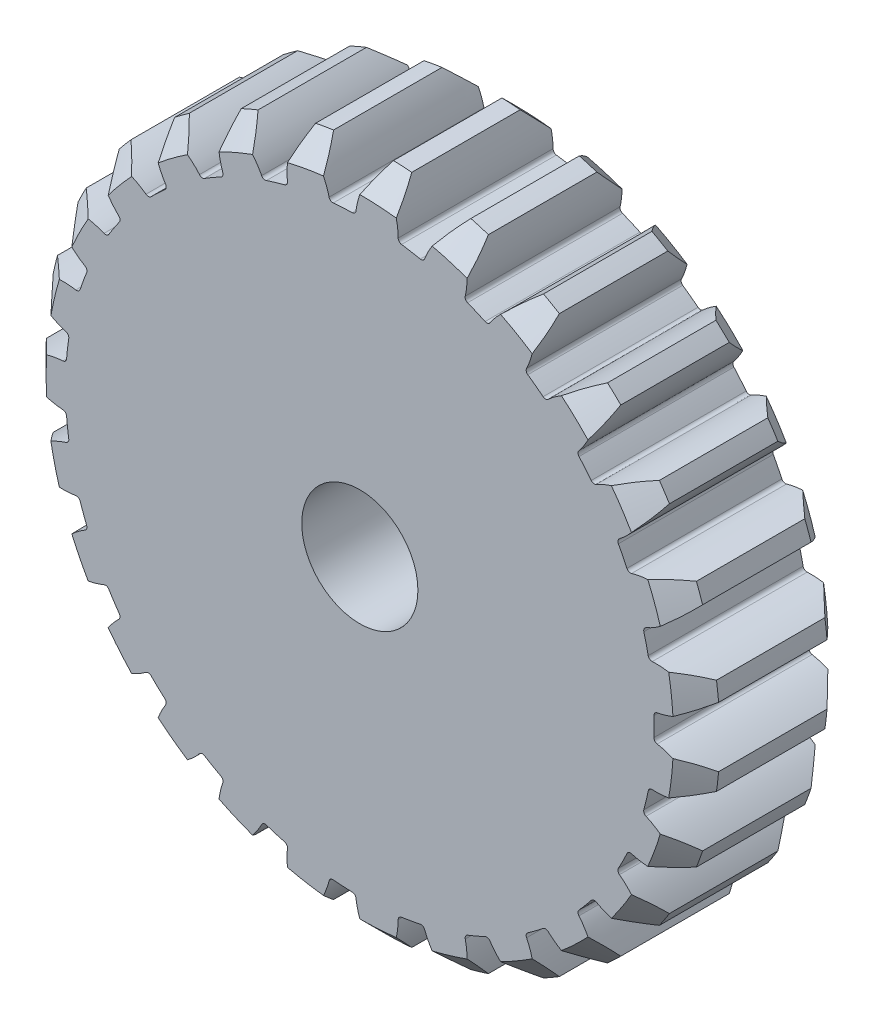
SolidWorks part; units mm, degrees
ref_plane "Piano frontale" through (0, 0, 0) normal (0, 0, 1) x (1, 0, 0)
ref_plane "Piano superiore" through (0, 0, 0) normal (0, 1, 0) x (1, 0, 0)
ref_plane "Piano destro" through (0, 0, 0) normal (1, 0, 0) x (0, 0, -1)
sketch "Schizzo1" plane through (0, 0, 0) normal (0, 0, 1) x (1, 0, 0)
  circle A0 centre (0, 0) radius 7.5
  circle A1 centre (0, 0) radius 43.5
  dimension "D1" = 15
  dimension "D2" = 87
extrude "Estrusione-Estrusione1" add sketch "Schizzo1" along normal blind 20
sketch "Schizzo2" plane through (0, 0, 20) normal (0, 0, 1) x (1, 0, 0)
  line L0 (0, 0) -> (37.9625, 1.6868) construction
  line L1 (0, 0) -> (37.9625, -1.6868) construction
  line L2 (0, 0) -> (38, 0) construction
  arc A0 (37.9625, -1.6868) -> (37.9625, 1.6868) centre (0, 0) ccw
  arc A1 (40.4318, -2.35) -> (40.4318, 2.35) centre (0, 0) ccw
  arc A2 (44.7366, -4.8617) -> (44.7366, 4.8617) centre (0, 0) ccw
  spline S0 degree 4 poles (37.9625, 1.6868) (37.9986, 1.6884) (38.0707, 1.6931) (38.2144, 1.7088) (38.5001, 1.7529) (38.8753, 1.8326) (39.3365, 1.9573) (39.9699, 2.1641) (40.6271, 2.4209) (41.3184, 2.7338) (42.2035, 3.1895) (43.2559, 3.8051) (44.5138, 4.6592) (46.3669, 6.1348) (48.8418, 8.5508) (51.5914, 12.0322) (54.2984, 16.7131) (56.4908, 22.1103) (57.9987, 27.7341) (58.8617, 33.4902) (59.1308, 39.5909) (58.6748, 47.1396) (56.9803, 56.0112) (53.5268, 65.9254) (48.7215, 74.9266) (43.7161, 82.0789) (38.0831, 88.7356) (32.9097, 93.8484) (27.3204, 98.5007) (21.3737, 102.6753) (16.4244, 105.723) (10.0249, 109.1628) (2.0466, 112.6932) (-5.5407, 115.2396) (-12.5934, 116.9916) (-17.5843, 117.9574) (-20.4494, 118.4351) (-23.3264, 118.839) (-26.2116, 119.1694) (-28.7446, 119.3946) (-30.9161, 119.5422) (-32.7324, 119.6351) (-34.177, 119.6915) (-35.5118, 119.7262) (-36.6834, 119.7452) (-37.7829, 119.7512) (-38.6472, 119.7508) (-39.7902, 119.7388) (-40.6059, 119.724) (-41.9398, 119.6899) (-42.9719, 119.6491) (-44.2237, 119.593) (-45.3491, 119.5278) (-46.8373, 119.4307) (-48.2798, 119.3155) (-49.7491, 119.1811) (-51.4921, 118.9978) (-53.2418, 118.7922) (-54.9815, 118.5591) (-56.7222, 118.2985) (-57.8777, 118.1102) (-58.4563, 118.0125) (-58.7447, 117.9628) knots 0 0 0 0 0 0.000701 0.001401 0.002802 0.005604 0.008133 0.010661 0.015718 0.019279 0.022839 0.02996 0.039347 0.048734 0.068727 0.096889 0.125051 0.153212 0.181374 0.209535 0.237696 0.271429 0.327752 0.384075 0.440398 0.46856 0.496721 0.553044 0.581206 0.609367 0.637529 0.66569 0.722013 0.778336 0.792417 0.806497 0.820578 0.834659 0.84874 0.86282 0.869861 0.876901 0.883942 0.890982 0.895509 0.900036 0.904564 0.909091 0.914773 0.920455 0.926136 0.931818 0.9375 0.943182 0.954545 0.960227 0.965909 0.977273 0.988636 0.994318 1 1 1 1 1 construction
  spline S1 degree 4 poles (37.9625, 1.6868) (37.9986, 1.6884) (38.0707, 1.6931) (38.2144, 1.7088) (38.5001, 1.7529) (38.8753, 1.8326) (39.3365, 1.9573) (39.9699, 2.1641) (40.6271, 2.4209) (41.3184, 2.7338) (42.2035, 3.1895) (43.1368, 3.7354) (43.8838, 4.2329) (44.4607, 4.6527) (44.7366, 4.8617) knots 0 0 0 0 0 0.000701 0.001401 0.002802 0.005604 0.008133 0.010661 0.015718 0.019279 0.022839 0.02996 0.036672 0.036672 0.036672 0.036672 0.036672
  spline S2 degree 4 poles (37.9625, -1.6868) (37.9986, -1.6884) (38.0707, -1.6931) (38.2144, -1.7088) (38.5001, -1.7529) (38.8753, -1.8326) (39.3365, -1.9573) (39.9699, -2.1641) (40.6271, -2.4209) (41.3184, -2.7338) (42.2035, -3.1895) (43.2559, -3.8051) (44.5138, -4.6592) (46.3669, -6.1348) (48.8418, -8.5508) (51.5914, -12.0322) (54.2984, -16.7131) (56.4908, -22.1103) (57.9987, -27.7341) (58.8617, -33.4902) (59.1308, -39.5909) (58.6748, -47.1396) (56.9803, -56.0112) (53.5268, -65.9254) (48.7215, -74.9266) (43.7161, -82.0789) (38.0831, -88.7356) (32.9097, -93.8484) (27.3204, -98.5007) (21.3737, -102.6753) (16.4244, -105.723) (10.0249, -109.1628) (2.0466, -112.6932) (-5.5407, -115.2396) (-12.5934, -116.9916) (-17.5843, -117.9574) (-20.4494, -118.4351) (-23.3264, -118.839) (-26.2116, -119.1694) (-28.7446, -119.3946) (-30.9161, -119.5422) (-32.7324, -119.6351) (-34.177, -119.6915) (-35.5118, -119.7262) (-36.6834, -119.7452) (-37.7829, -119.7512) (-38.6472, -119.7508) (-39.7902, -119.7388) (-40.6059, -119.724) (-41.9398, -119.6899) (-42.9719, -119.6491) (-44.2237, -119.593) (-45.3491, -119.5278) (-46.8373, -119.4307) (-48.2798, -119.3155) (-49.7491, -119.1811) (-51.4921, -118.9978) (-53.2418, -118.7922) (-54.9815, -118.5591) (-56.7222, -118.2985) (-57.8777, -118.1102) (-58.4563, -118.0125) (-58.7447, -117.9628) knots 0 0 0 0 0 0.000701 0.001401 0.002802 0.005604 0.008133 0.010661 0.015718 0.019279 0.022839 0.02996 0.039347 0.048734 0.068727 0.096889 0.125051 0.153212 0.181374 0.209535 0.237696 0.271429 0.327752 0.384075 0.440398 0.46856 0.496721 0.553044 0.581206 0.609367 0.637529 0.66569 0.722013 0.778336 0.792417 0.806497 0.820578 0.834659 0.84874 0.86282 0.869861 0.876901 0.883942 0.890982 0.895509 0.900036 0.904564 0.909091 0.914773 0.920455 0.926136 0.931818 0.9375 0.943182 0.954545 0.960227 0.965909 0.977273 0.988636 0.994318 1 1 1 1 1 construction
  spline S3 degree 4 poles (37.9625, -1.6868) (37.9986, -1.6884) (38.0707, -1.6931) (38.2144, -1.7088) (38.5001, -1.7529) (38.8753, -1.8326) (39.3365, -1.9573) (39.9699, -2.1641) (40.6271, -2.4209) (41.3184, -2.7338) (42.2035, -3.1895) (43.1368, -3.7354) (43.8838, -4.2329) (44.4607, -4.6527) (44.7366, -4.8617) knots 0 0 0 0 0 0.000701 0.001401 0.002802 0.005604 0.008133 0.010661 0.015718 0.019279 0.022839 0.02996 0.036672 0.036672 0.036672 0.036672 0.036672
  dimension "D1" = 76
  dimension "D2" = 81
  dimension "D3" = 90
  dimension "D4" = 4.7
extrude "Taglio-Estrusione1" cut sketch "Schizzo2" against normal blind 20 contours A2 S1 A0 S3
fillet "Raccordo1" radius 0.5 2 edges at (37.9625, 1.6868, 10) (37.9625, -1.6868, 10)
chamfer "Smusso1" distance 3 angle 45 2 edges at (-43.5, 0, 20) (-43.5, 0, 0)
pattern_circular "RipetizioneCircolare1" count 27 over 360 about axis through (0, 0, 20) along (0, 0, -1) of "Taglio-Estrusione1", "Raccordo1"
